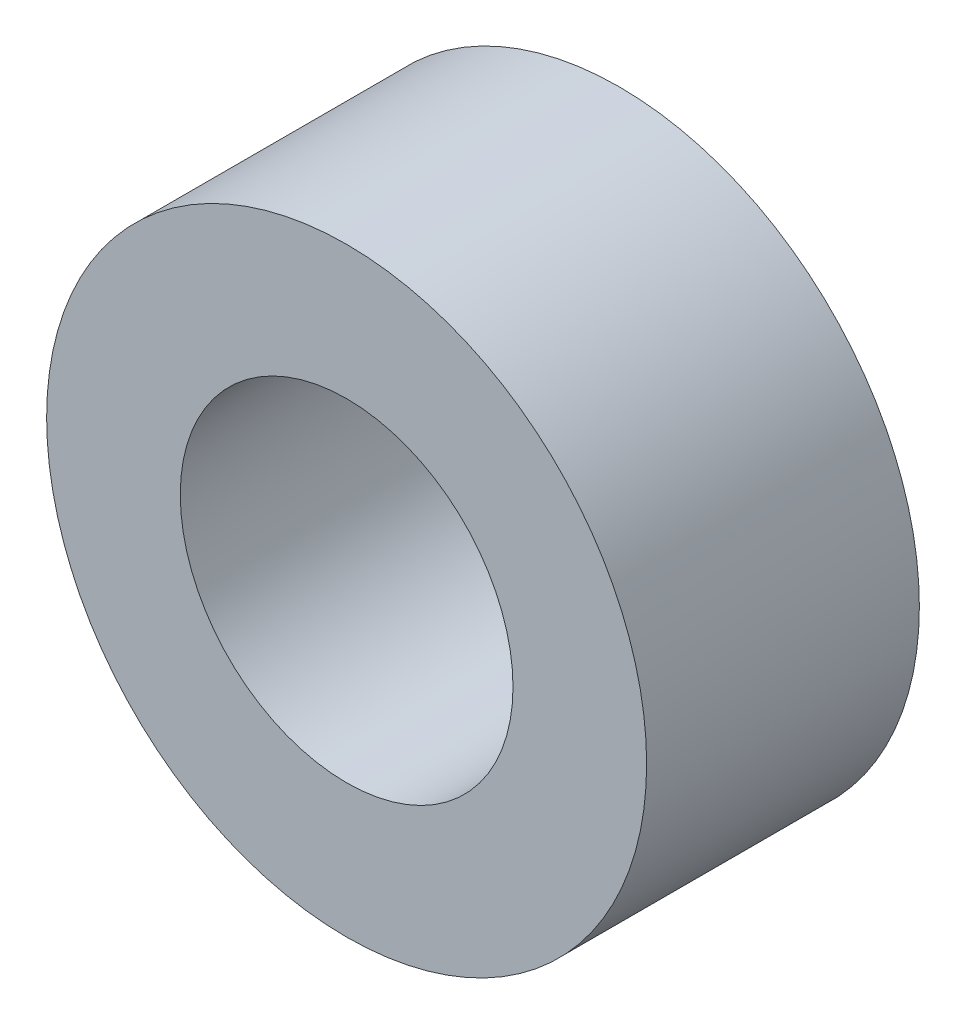
SolidWorks part; units mm, degrees
ref_plane "前视基准面" through (0, 0, 0) normal (0, 0, 1) x (1, 0, 0)
ref_plane "上视基准面" through (0, 0, 0) normal (0, 1, 0) x (1, 0, 0)
ref_plane "右视基准面" through (0, 0, 0) normal (1, 0, 0) x (0, 0, -1)
other "Configuration Table"
sketch "草图1" plane through (0, 0, 0) normal (0, 0, 1) x (1, 0, 0)
  circle A0 centre (0, 0) radius 5.5
  circle A1 centre (0, 0) radius 3.05
  dimension "D1" = 6.1
  dimension "D2" = 11
extrude "凸台-拉伸1" add sketch "草图1" along normal blind 5
